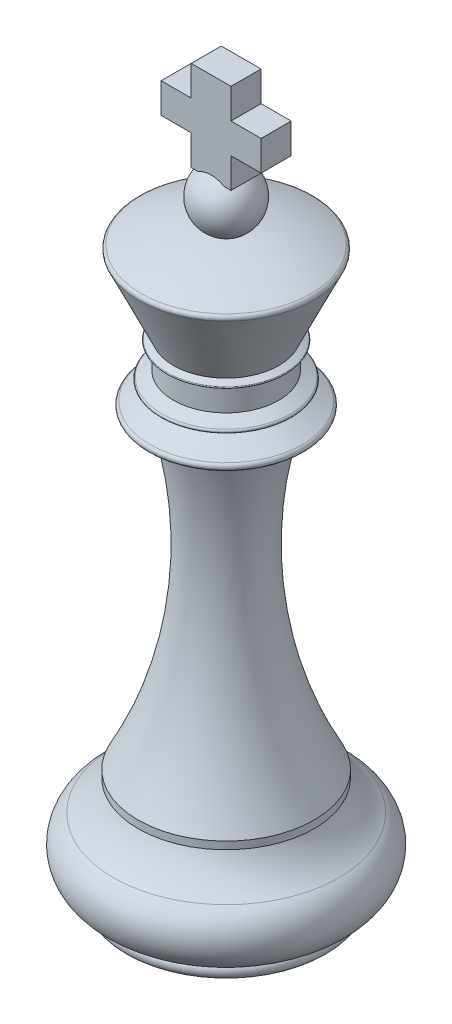
SolidWorks part; units mm, degrees
ref_plane "Front Plane" through (0, 0, 0) normal (0, 0, 1) x (1, 0, 0)
ref_plane "Top Plane" through (0, 0, 0) normal (0, 1, 0) x (1, 0, 0)
ref_plane "Right Plane" through (0, 0, 0) normal (1, 0, 0) x (0, 0, -1)
sketch "Sketch1" plane through (0, 0, 0) normal (0, 0, 1) x (1, 0, 0)
  line L0 (0, 91.1599) -> (0, -98.6095) construction
  line L1 (0, 0) -> (12.5, 0)
  line L2 (11.7066, 14) -> (11.7066, 15)
  line L3 (7, 55) -> (10.1056, 56.5528)
  line L4 (10.1056, 57.4472) -> (7, 59)
  line L5 (4.4414, 57) -> (15.9327, 57) construction
  line L6 (7, 59) -> (8.5528, 59.7764)
  line L7 (8.5528, 60.2236) -> (7, 61)
  line L8 (10.5003, 60) -> (3.7165, 60) construction
  line L9 (7, 61) -> (7, 64)
  line L10 (7, 64) -> (7.8211, 64.4106)
  line L11 (7.8211, 64.5894) -> (7, 65)
  line L12 (9.1695, 64.5) -> (3.9698, 64.5) construction
  line L13 (7, 65) -> (11.5638, 74.7871)
  line L14 (0, 0) -> (0, 85)
  arc A0 (12.5, 0) -> (12.5, 2) centre (12.5, 1) ccw
  arc A1 (12.5, 2) -> (15, 10) centre (12.5, 6.3906) ccw
  arc A2 (15, 10) -> (11.7066, 14) centre (20.4093, 17.8096) cw
  arc A3 (11.7066, 15) -> (7, 55) centre (60.1833, 40.9809) cw
  arc A4 (11.3141, 75.4551) -> (2.4527, 77.8402) centre (-0.6903, 48.5081) ccw
  arc A5 (0, 85) -> (2.4527, 77.8402) centre (0, 81) cw
  arc A6 (11.7769, 75.2442) -> (0, 78) centre (-0.6903, 48.5081) ccw construction
  arc A7 (11.5638, 74.7871) -> (11.3141, 75.4551) centre (11.1106, 74.9984) ccw
  arc A8 (7.8211, 64.4106) -> (7.8211, 64.5894) centre (7.7764, 64.5) ccw
  arc A9 (8.5528, 59.7764) -> (8.5528, 60.2236) centre (8.441, 60) ccw
  arc A10 (10.1056, 56.5528) -> (10.1056, 57.4472) centre (9.882, 57) ccw
  point P39 (8, 64.5)
  point P42 (9, 60)
  point P45 (11, 57)
  dimension "D1" = 1
  dimension "D4" = 15
  dimension "D5" = 9.5
  dimension "D8" = 55
  dimension "D20" = 29.5
  dimension "D21" = 4
  dimension "D23" = 0.5
  dimension "D24" = 0.1
  dimension "D25" = 0.25
  dimension "D26" = 0.5
  dimension "D2" = 12.5
  dimension "D3" = 10
  dimension "D6" = 14
  dimension "D7" = 1
  dimension "D9" = 55
  dimension "D10" = 7
  dimension "D11" = 11
  dimension "D12" = 4
  dimension "D13" = 2
  dimension "D14" = 2
  dimension "D15" = 3
  dimension "D16" = 1
  dimension "D17" = 1
  dimension "D18" = 25
  dimension "D19" = 13
  dimension "D22" = 16
revolve "Revolve1" add sketch "Sketch1" angle 360 about L0
sketch "Sketch3" plane through (0, 0, 0) normal (0, 0, 1) x (1, 0, 0)
  line L0 (0, 85) -> (0, 107) construction
  line L1 (-2.646, 84) -> (2.646, 84)
  line L2 (2.646, 84) -> (2.646, 88)
  line L3 (2.646, 88) -> (6.646, 88)
  line L4 (6.646, 88) -> (6.646, 92)
  line L5 (6.646, 92) -> (2.646, 92)
  line L6 (2.646, 92) -> (2.646, 96)
  line L7 (2.646, 96) -> (-2.646, 96)
  line L8 (-2.646, 84) -> (-2.646, 88)
  line L9 (-2.646, 88) -> (-6.646, 88)
  line L10 (-6.646, 88) -> (-6.646, 92)
  line L11 (-6.646, 92) -> (-2.646, 92)
  line L12 (-2.646, 92) -> (-2.646, 96)
  arc A0 (2.4527, 77.8402) -> (-2.4527, 77.8402) centre (0, 81) ccw construction
  point P15 (0, 84)
  point P20 (0, 96)
  dimension "D1" = 1
  dimension "D2" = 2.646
  dimension "D3" = 4
  dimension "D4" = 4
  dimension "D5" = 4
  dimension "D6" = 4
extrude "Boss-Extrude2" add sketch "Sketch3" along normal mid plane 4
